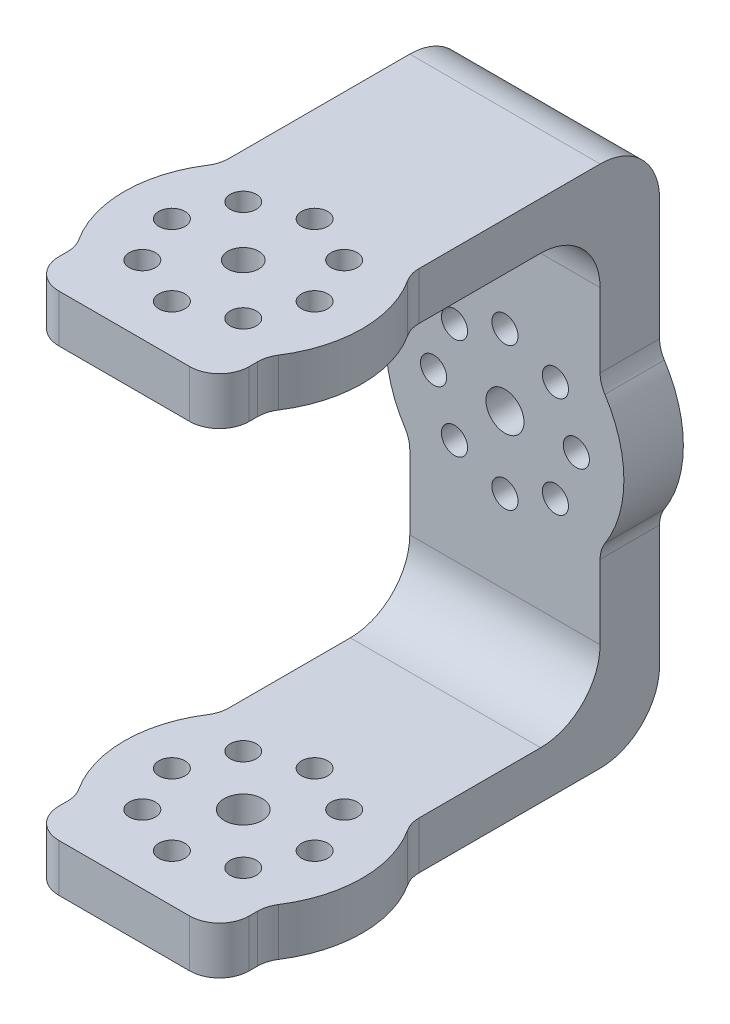
SolidWorks part; units mm, degrees
material "ABS"
ref_plane "正面" through (0, 0, 0) normal (0, 0, 1) x (1, 0, 0)
ref_plane "平面" through (0, 0, 0) normal (0, 1, 0) x (1, 0, 0)
ref_plane "右側面" through (0, 0, 0) normal (1, 0, 0) x (0, 0, -1)
sketch "ｽｹｯﾁ1" plane through (0, 0, 0) normal (0, 0, 1) x (1, 0, 0)
  line L0 (0, 0) -> (0, 36) construction
  line L1 (-8, 0) -> (8, 0)
  line L2 (-8, 0) -> (-8, 12)
  line L3 (-8, 36) -> (8, 36)
  line L4 (8, 0) -> (8, 12)
  line L5 (-8, 24) -> (-8, 36)
  line L6 (8, 24) -> (8, 36)
  circle A0 centre (0, 18) radius 6 construction
  circle A1 centre (0, 18) radius 1.6
  circle A2 centre (0, 24) radius 1.1
  circle A3 centre (4.2426, 22.2426) radius 1.1
  circle A4 centre (6, 18) radius 1.1
  circle A5 centre (4.2426, 13.7574) radius 1.1
  circle A6 centre (0, 12) radius 1.1
  circle A7 centre (-4.2426, 13.7574) radius 1.1
  circle A8 centre (-6, 18) radius 1.1
  circle A9 centre (-4.2426, 22.2426) radius 1.1
  arc A10 (-8, 24) -> (-8, 12) centre (0, 18) ccw
  arc A11 (8, 12) -> (8, 24) centre (0, 18) ccw
  point P29 (0, 18)
  dimension "D3" = 3.2
  dimension "D4" = 12
  dimension "D5" = 2.2
  dimension "D7" = 20
  dimension "D1" = 16
  dimension "D2" = 36
  dimension "D6" = 8
extrude "ﾎﾞｽ - 押し出し1" add sketch "ｽｹｯﾁ1" along normal blind 5
sketch "ｽｹｯﾁ2" plane through (0, 0, 0) normal (0, -1, 0) x (1, 0, 0)
  line L0 (8, 5) -> (8, 0) construction
  line L1 (-8, 0) -> (8, 0)
  line L2 (-8, 0) -> (-8, 21)
  line L3 (-8, 37) -> (8, 37)
  line L4 (8, 0) -> (8, 21)
  line L5 (0, 37) -> (0, 0) construction
  line L6 (-8, 33) -> (-8, 37)
  line L7 (8, 33) -> (8, 37)
  circle A0 centre (0, 27) radius 1.6
  circle A1 centre (0, 27) radius 6 construction
  circle A2 centre (6, 27) radius 1.1
  circle A3 centre (4.2426, 22.7574) radius 1.1
  circle A4 centre (0, 21) radius 1.1
  circle A5 centre (-4.2426, 22.7574) radius 1.1
  circle A6 centre (-6, 27) radius 1.1
  circle A7 centre (-4.2426, 31.2426) radius 1.1
  circle A8 centre (0, 33) radius 1.1
  circle A9 centre (4.2426, 31.2426) radius 1.1
  arc A10 (-8, 33) -> (-8, 21) centre (0, 27) ccw
  arc A11 (8, 21) -> (8, 33) centre (0, 27) ccw
  point P32 (0, 27)
  dimension "D2" = 12
  dimension "D3" = 3.2
  dimension "D5" = 2.2
  dimension "D7" = 10
  dimension "D1" = 37
  dimension "D4" = 10
  dimension "D6" = 8
extrude "ﾎﾞｽ - 押し出し2" add sketch "ｽｹｯﾁ2" along normal blind 4
sketch "ｽｹｯﾁ3" plane through (0, 36, 0) normal (0, 1, 0) x (1, 0, 0)
  line L0 (8, -5) -> (8, 0)
  line L1 (8, 0) -> (-8, 0)
  line L2 (-8, 0) -> (-8, -5)
  line L6 (8, -5) -> (-8, -5)
  line L7 (-8, -5) -> (-8, -21)
  line L8 (-8, -33) -> (-8, -37)
  line L9 (-8, -37) -> (8, -37)
  line L10 (8, -37) -> (8, -33)
  line L11 (8, -21) -> (8, -5)
  line L13 (-8, -5) -> (-8, -21)
  line L14 (-8, -33) -> (-8, -37)
  line L15 (-8, -37) -> (8, -37)
  line L16 (8, -37) -> (8, -33)
  line L17 (8, -21) -> (8, -5)
  circle A0 centre (4.2426, -22.7574) radius 1.1 construction
  circle A1 centre (0, -21) radius 1.1 construction
  arc A2 (-8, -21) -> (-8, -33) centre (0, -27) ccw
  arc A3 (8, -33) -> (8, -21) centre (0, -27) ccw
  arc A4 (-8, -21) -> (-8, -33) centre (0, -27) ccw
  arc A5 (8, -33) -> (8, -21) centre (0, -27) ccw
  circle A6 centre (-4.2426, -22.7574) radius 1.1 construction
  circle A7 centre (-6, -27) radius 1.1 construction
  circle A8 centre (-4.2426, -31.2426) radius 1.1 construction
  circle A9 centre (0, -33) radius 1.1 construction
  circle A10 centre (4.2426, -31.2426) radius 1.1 construction
  circle A11 centre (6, -27) radius 1.1 construction
  circle A12 centre (4.2426, -22.7574) radius 1.1
  circle A13 centre (0, -21) radius 1.1
  circle A14 centre (-4.2426, -22.7574) radius 1.1
  circle A15 centre (-6, -27) radius 1.1
  circle A16 centre (-4.2426, -31.2426) radius 1.1
  circle A17 centre (0, -33) radius 1.1
  circle A18 centre (4.2426, -31.2426) radius 1.1
  circle A19 centre (6, -27) radius 1.1
  circle A20 centre (0, -27) radius 1.3
  dimension "D2" = 2.6
  dimension "D1" = 0
extrude "ﾎﾞｽ - 押し出し3" add sketch "ｽｹｯﾁ3" along normal blind 4
fillet "ﾌｨﾚｯﾄ1" radius 5 4 edges at (0, 40, 0) (0, -4, 0) (0, 0, 5) (0, 36, 5)
fillet "ﾌｨﾚｯﾄ2" radius 2.5 16 edges at (8, 24, 2.5) (8, 12, 2.5) (8, 38, 21) (8, 38, 33) (8, 38, 37) (-8, 38, 37) (-8, 38, 33) (-8, 38, 21) (-8, 24, 2.5) (-8, 12, 2.5) (-8, -2, 21) (-8, -2, 33) (-8, -2, 37) (8, -2, 37) (8, -2, 21) (8, -2, 33)
